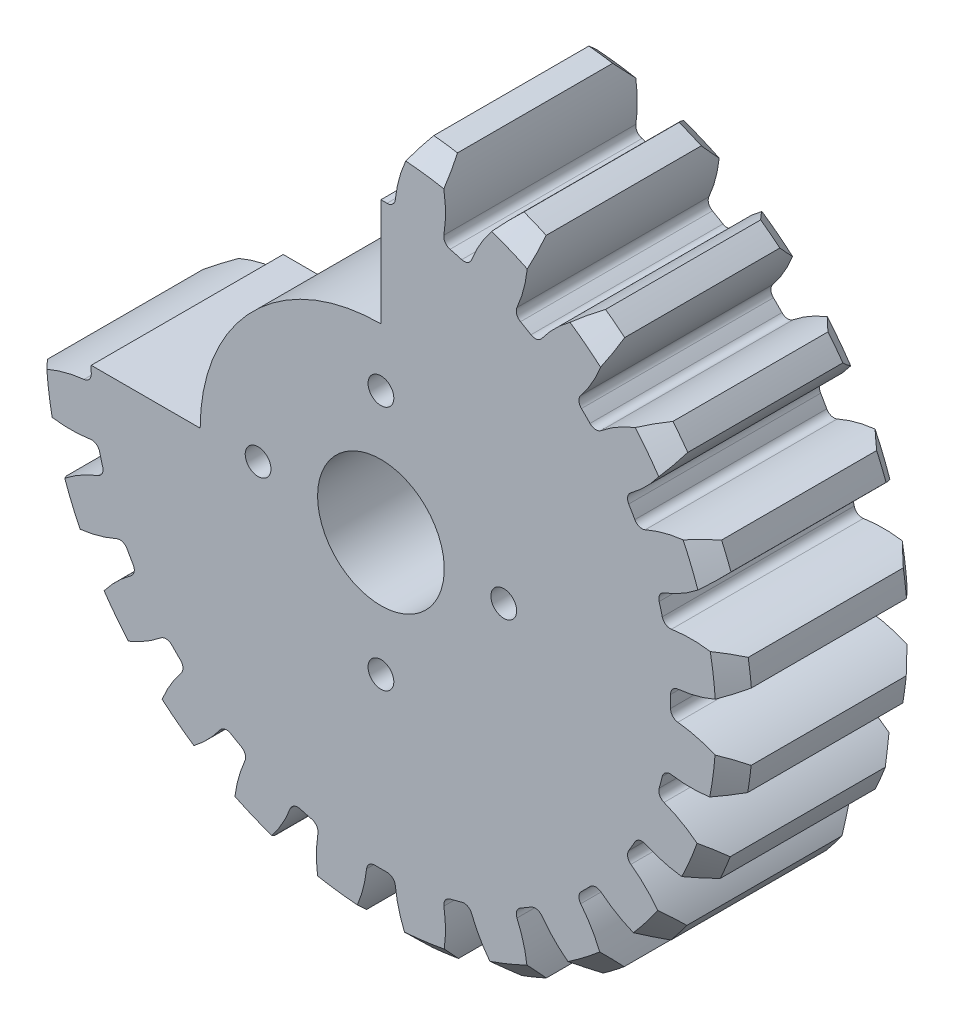
SolidWorks part; units mm, degrees
ref_plane "Plan de face" through (0, 0, 0) normal (0, 0, 1) x (1, 0, 0)
ref_plane "Plan de dessus" through (0, 0, 0) normal (0, 1, 0) x (1, 0, 0)
ref_plane "Plan de droite" through (0, 0, 0) normal (1, 0, 0) x (0, 0, -1)
sketch "Sketch1" plane through (0, 0, 0) normal (0, 0, 1) x (1, 0, 0)
  circle A0 centre (0, 0) radius 21.25 construction
  circle A1 centre (0, 0) radius 23.0208
  dimension "D1" = 42.5
  dimension "D2" = 46.0417
extrude "Boss-Extrude1" add sketch "Sketch1" along normal mid plane 12.5
sketch "Sketch2" plane through (0, 0, 6.25) normal (0, 0, 1) x (1, 0, 0)
  line L0 (0, 23.0208) -> (0, 0) construction
  line L1 (0, 0) -> (5.9582, 22.2364) construction
  line L2 (0, 0) -> (3.0048, 22.8239) construction
  line L3 (-0.8962, 18.7494) -> (0, 0) construction
  line L4 (-1.3898, 21.2045) -> (1.3898, 21.2045) construction
  line L5 (1.3898, 21.2045) -> (4.1457, 20.8417) construction
  line L6 (-2.0186, 22.9322) -> (0, 17.386) construction
  arc A0 (0.8962, 18.7494) -> (-0.8962, 18.7494) centre (0, 0) ccw
  circle A1 centre (0, 0) radius 19.4792 construction
  circle A2 centre (0, 0) radius 23.0208 construction
  arc A3 (2.2433, 22.9113) -> (0.8962, 18.7494) centre (9.2295, 18.3511) ccw
  arc A4 (-2.2433, 22.9113) -> (-0.8962, 18.7494) centre (-9.2295, 18.3511) cw
  circle A5 centre (0, 0) radius 23.0208 construction
  circle A6 centre (0, 0) radius 21.25 construction
  arc A7 (-2.2433, 22.9113) -> (2.2433, 22.9113) centre (0, 0) cw
  dimension "D1" = 15
  dimension "D2" = 3.5417
  dimension "D3" = 4.25
  dimension "D4" = 20
extrude "Cut-Extrude1" cut sketch "Sketch2" against normal through all
fillet "Fillet1" radius 0.5312 2 edges at (0.8962, 18.7494, 0) (-0.8962, 18.7494, 0)
chamfer "Chamfer1" distance 1.2 2 edges at (0, -23.0208, 6.25) (0, -23.0208, -6.25)
pattern_circular "CirPattern2" count 24 over 360 about axis through (0, -0.0957, 0) along (0, 0, 1) of "Fillet1", "Cut-Extrude1"
sketch "Sketch3" plane through (0, 0, -6.25) normal (0, 0, -1) x (-1, 0, 0)
  circle A0 centre (0, 0) radius 4.125
  circle A1 centre (0, 0) radius 8 construction
  circle A2 centre (0, 8) radius 0.8387
  circle A3 centre (8, 0) radius 0.8387
  circle A4 centre (0, -8) radius 0.8387
  circle A5 centre (-8, 0) radius 0.8387
  dimension "D1" = 8.25
  dimension "D2" = 16
  dimension "D3" = 1.6774
extrude "Cut-Extrude2" cut sketch "Sketch3" against normal through all
sketch "Sketch4" plane through (0, 0, -6.25) normal (0, 0, -1) x (-1, 0, 0)
  line L0 (0, 0) -> (0, 23.0208) construction
  line L1 (0, 0) -> (23.0208, 0) construction
  line L6 (11.7708, 0) -> (23.0208, 0)
  line L7 (0, 11.7708) -> (0, 23.0208)
  arc A2 (0, 11.7708) -> (11.7708, 0) centre (0, 0) cw
  circle A3 centre (0, 0) radius 23.0208 construction
  arc A5 (0, 23.0208) -> (23.0208, 0) centre (0, 0) cw
  dimension "D1" = 11.25
extrude "Cut-Extrude3" cut sketch "Sketch4" against normal through all
equation "\"Module\"= ( 4.25 / \"Number of teeth\" )"
equation "\"Number of teeth\"= 24"
equation "\"Pressure angle\"= 20"
equation "\"D1@Sketch1\"=\"Module\" * \"Number of teeth\""
equation "\"D2@Sketch1\"=(\"Number of teeth\" + 2) * \"Module\""
equation "\"D2@Sketch2\"=\"Module\"*2"
equation "\"D1@Fillet1\"=0.3*\"Module\""
equation "\"D1@Sketch2\"=360/\"Number of teeth\""
equation "\"D3@Sketch2\"=\"Module\"*2.4"
equation "\"D4@Sketch2\"=\"Pressure angle\""
equation "\"D1@CirPattern2\"=\"Number of teeth\""
